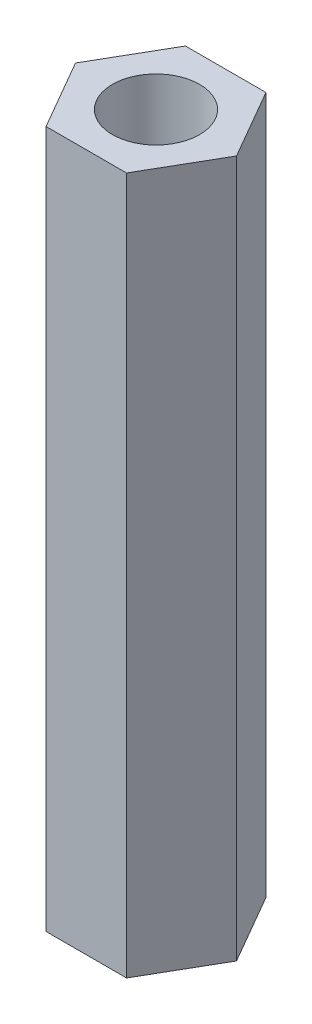
SolidWorks part; units mm, degrees
ref_plane "Front Plane" through (0, 0, 0) normal (0, 0, 1) x (1, 0, 0)
ref_plane "Top Plane" through (0, 0, 0) normal (0, 1, 0) x (1, 0, 0)
ref_plane "Right Plane" through (0, 0, 0) normal (1, 0, 0) x (0, 0, -1)
sketch "Sketch1" plane through (0, 0, 0) normal (0, 1, 0) x (1, 0, 0)
  line L1 (2.3094, 0) -> (1.1547, 2)
  line L2 (1.1547, 2) -> (-1.1547, 2)
  line L3 (-1.1547, 2) -> (-2.3094, 0)
  line L4 (-2.3094, 0) -> (-1.1547, -2)
  line L5 (-1.1547, -2) -> (1.1547, -2)
  line L6 (1.1547, -2) -> (2.3094, 0)
  circle A0 centre (0, 0) radius 2 construction
  dimension "D1" = 4
extrude "Boss-Extrude1" add sketch "Sketch1" along normal blind 20
hole_wizard "M3x0.5 Tapped Hole1" positions "Sketch4" profile "Sketch3" tap size "M3x0.5" standard "ANSI Metric" end condition through all
sketch "Sketch4" plane through (0, 0, 0) normal (0, -1, 0) x (-1, 0, 0)
  point P0 (0, 0)
sketch "Sketch3" plane through (0, 0, 0) normal (1, 0, 0) x (0, 0, -1)
  line L0 (0, 0) -> (0, 20)
  line L1 (0, 20) -> (1.25, 20)
  line L2 (1.25, 20) -> (1.25, 0)
  line L5 (1.25, 0) -> (0, 0)
  line L11 (0, -6.35) -> (0, 107.95) construction
  dimension "Thru Tap Drill Dia." = 2.5
  dimension "Thru Tap Drill Depth" = 20
cosmetic thread "Hole Thread1"
